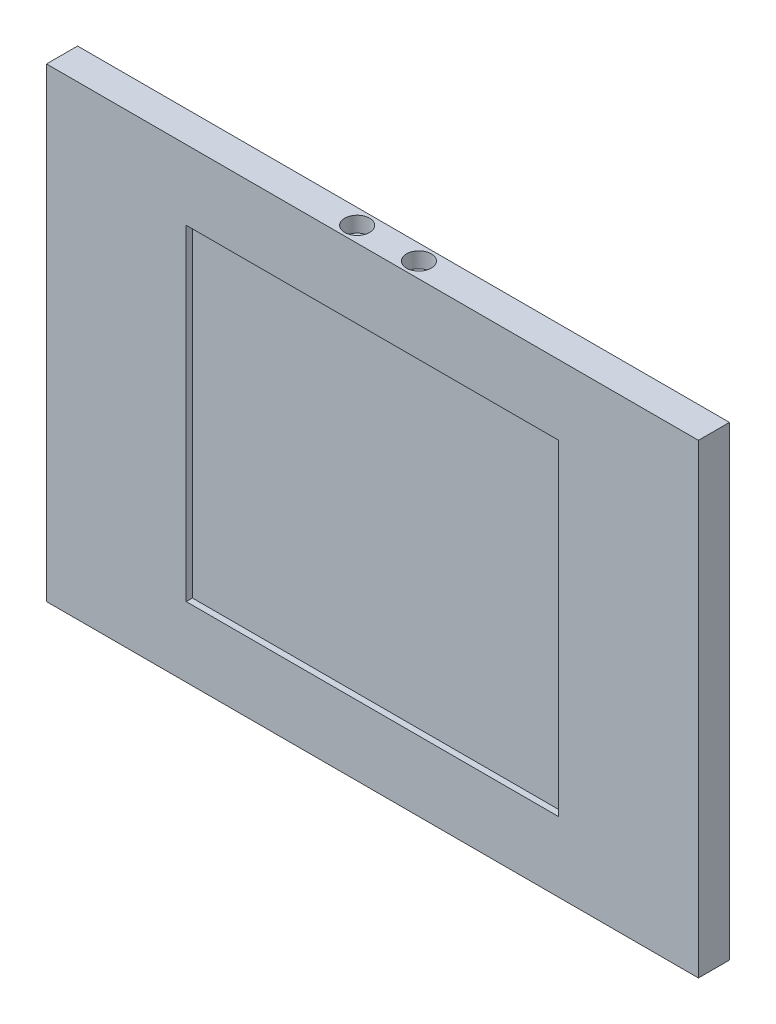
SolidWorks part; units mm, degrees
material "Balsa"
ref_plane "Plan de face" through (0, 0, 0) normal (0, 0, 1) x (1, 0, 0)
ref_plane "Plan de dessus" through (0, 0, 0) normal (0, 1, 0) x (1, 0, 0)
ref_plane "Plan de droite" through (0, 0, 0) normal (1, 0, 0) x (0, 0, -1)
sketch "Sketch1" plane through (0, 0, 0) normal (0, 0, 1) x (1, 0, 0)
  line L1 (-105, -75) -> (105, -75)
  line L2 (-105, -75) -> (-105, 75)
  line L3 (-105, 75) -> (105, 75)
  line L4 (105, -75) -> (105, 75)
  line L5 (-105, -75) -> (105, 75) construction
  line L6 (-105, 75) -> (105, -75) construction
  point P0 (0, 0)
  dimension "D1" = 210
  dimension "D2" = 150
extrude "Boss-Extrude1" add sketch "Sketch1" along normal blind 10
sketch "Sketch2" plane through (0, 0, 10) normal (0, 0, 1) x (1, 0, 0)
  line L0 (105, -75) -> (105, 75) construction
  line L1 (-60, -52.5) -> (60, -52.5)
  line L2 (-60, -52.5) -> (-60, 52.5)
  line L3 (-60, 52.5) -> (60, 52.5)
  line L4 (60, -52.5) -> (60, 52.5)
  line L5 (-60, -52.5) -> (60, 52.5) construction
  line L6 (-60, 52.5) -> (60, -52.5) construction
  line L8 (105, 75) -> (-105, 75) construction
  point P0 (0, 0)
  dimension "D1" = 45
  dimension "D2" = 22.5
extrude "Cut-Extrude1" cut sketch "Sketch2" against normal blind 2
sketch "Sketch3" plane through (0, 75, 0) normal (0, 1, 0) x (1, 0, 0)
  line L3 (-20, 27.1766) -> (-20, -49.4519) construction
  line L4 (-105, -10) -> (-105, 0) construction
  line L5 (20, 27.1766) -> (20, -49.4519) construction
  line L6 (105, -10) -> (105, 0) construction
  line L7 (0, 27.1766) -> (0, -47.3962) construction
  line L8 (105, 0) -> (-105, 0) construction
  circle A0 centre (-9.9428, -5) radius 4
  circle A1 centre (9.9428, -5) radius 4
  dimension "D4" = 8
  dimension "D1" = 85
  dimension "D2" = 85
  dimension "D3" = 5
extrude "Cut-Extrude2" cut sketch "Sketch3" against normal blind 5
